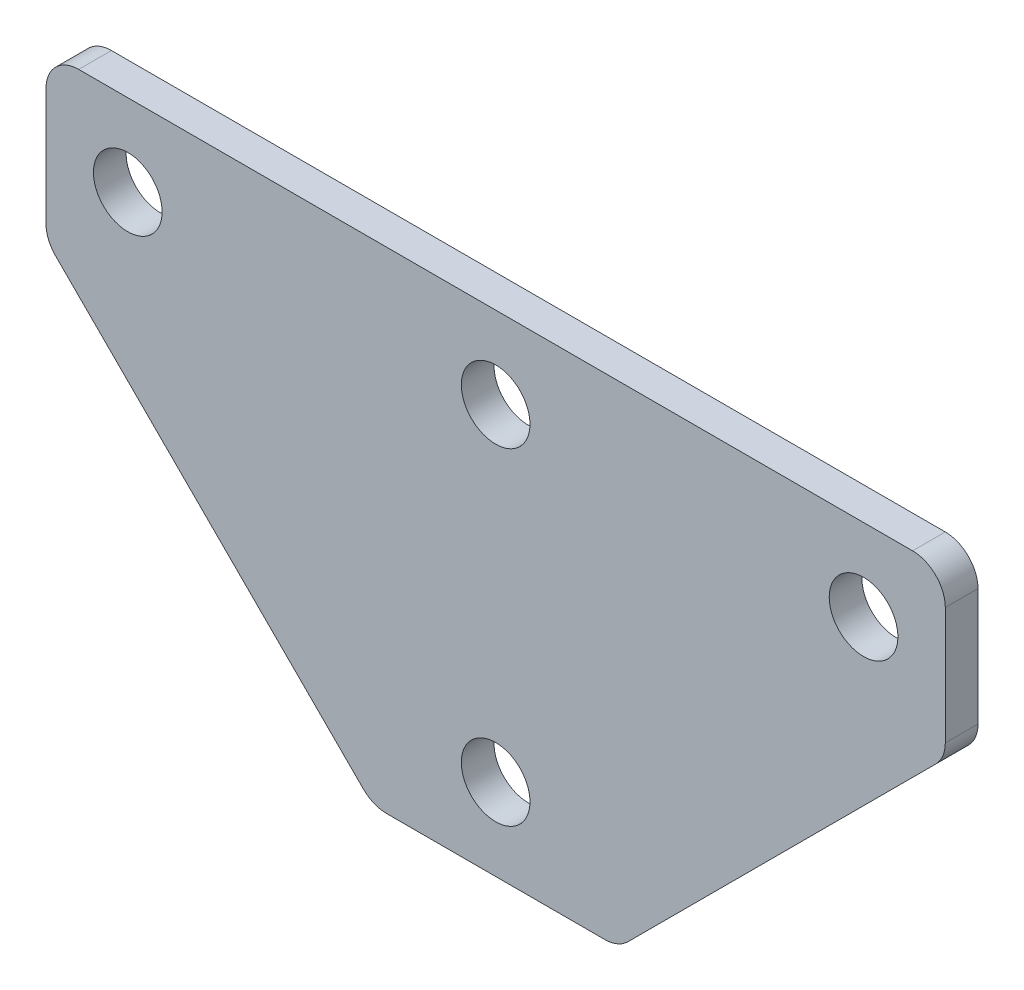
SolidWorks part; units mm, degrees
material "5052-H34"
ref_plane "正面" through (0, 0, 0) normal (0, 0, 1) x (1, 0, 0)
ref_plane "平面" through (0, 0, 0) normal (0, 1, 0) x (1, 0, 0)
ref_plane "右側面" through (0, 0, 0) normal (1, 0, 0) x (0, 0, -1)
sketch "ｽｹｯﾁ1" plane through (0, 0, 0) normal (0, 0, 1) x (1, 0, 0)
  line L0 (0, 0) -> (15, 0)
  line L1 (15, 0) -> (35, 20)
  line L2 (35, 20) -> (35, 30)
  line L3 (35, 30) -> (-20, 30)
  line L4 (-20, 30) -> (-20, 20)
  line L5 (-20, 20) -> (0, 0)
  line L6 (7.5, 30) -> (7.5, 0) construction
  line L7 (-20, 25) -> (35, 25) construction
  circle A0 centre (-15, 25) radius 2.1
  circle A1 centre (30, 25) radius 2.1
  circle A2 centre (7.5, 25) radius 2.1
  circle A3 centre (7.5, 5) radius 2.1
  dimension "D5" = 4.2
  dimension "D6" = 5
  dimension "D7" = 4.2
  dimension "D8" = 5
  dimension "D1" = 10
  dimension "D2" = 15
  dimension "D3" = 30
  dimension "D4" = 55
extrude "ﾎﾞｽ - 押し出し1" add sketch "ｽｹｯﾁ1" along normal blind 2
fillet "ﾌｨﾚｯﾄ1" radius 2 6 edges at (0, 0, 1) (15, 0, 1) (35, 20, 1) (35, 30, 1) (-20, 20, 1) (-20, 30, 1)
